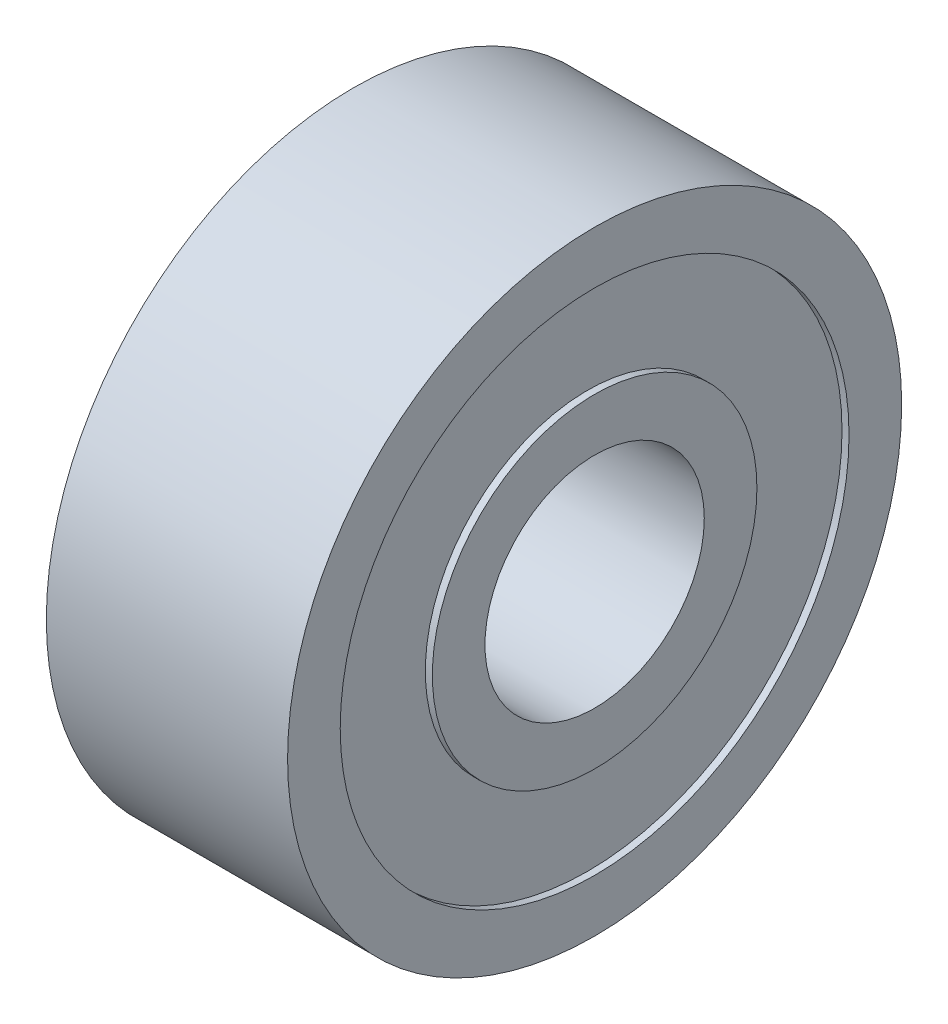
SolidWorks part; units mm, degrees
material "AISI 304"
ref_plane "Front Plane" through (0, 0, 0) normal (0, 0, 1) x (1, 0, 0)
ref_plane "Top Plane" through (0, 0, 0) normal (0, 1, 0) x (1, 0, 0)
ref_plane "Right Plane" through (0, 0, 0) normal (1, 0, 0) x (0, 0, -1)
sketch "Sketch1" plane through (0, 0, 0) normal (1, 0, 0) x (0, 0, -1)
  circle A0 centre (0, 0) radius 3.9688
  circle A1 centre (0, 0) radius 11.1125
  dimension "D1" = 7.9375
  dimension "D2" = 22.225
extrude "Boss-Extrude1" add sketch "Sketch1" along normal mid plane 8.7312
sketch "Sketch2" plane through (4.3656, 0, 0) normal (1, 0, 0) x (0, 0, -1)
  circle A0 centre (0, 0) radius 5.8737
  circle A1 centre (0, 0) radius 9.2075
  circle A2 centre (0, 0) radius 11.1125 construction
  circle A3 centre (0, 0) radius 3.9688 construction
  dimension "D1" = 1.905
  dimension "D2" = 1.905
extrude "Cut-Extrude1" cut sketch "Sketch2" against normal blind 0.254
mirror "Mirror1" about plane through (0, 0, 0) normal (1, 0, 0) of "Cut-Extrude1"
